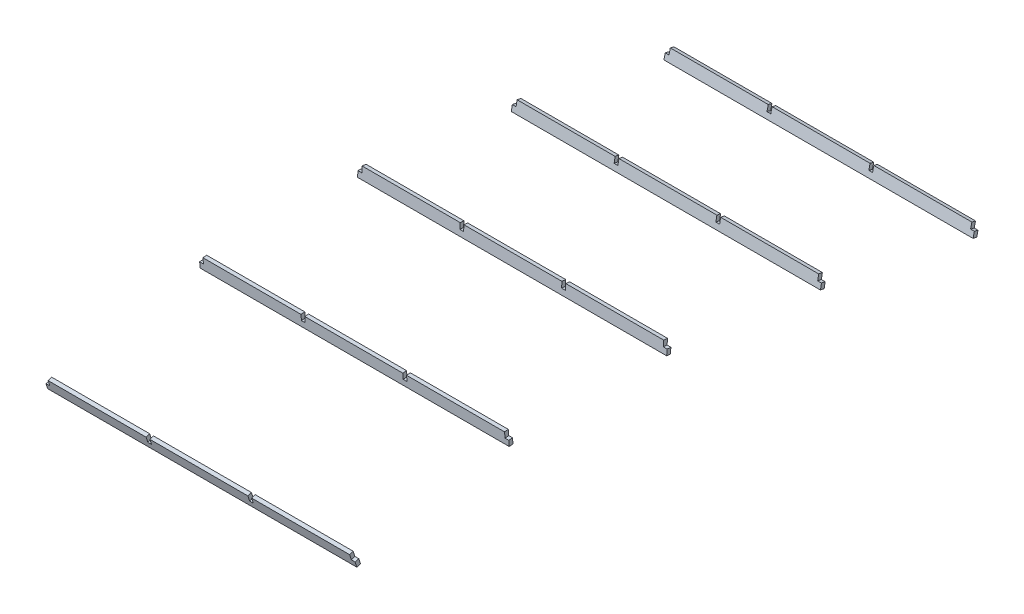
SolidWorks part; units mm, degrees
material "Balsa"
ref_plane "Front" through (0, 0, 0) normal (0, 0, 1) x (1, 0, 0)
ref_plane "Top" through (0, 0, 0) normal (0, 1, 0) x (1, 0, 0)
ref_plane "Right" through (0, 0, 0) normal (1, 0, 0) x (0, 0, -1)
sketch "Sketch1" plane through (0, 0, 0) normal (1, 0, 0) x (0, 0, -1)
  line L0 (603.9897, 31.1863) -> (568.0177, -122.1933) construction
  line L1 (474.8438, 58.0051) -> (472.6476, 45.4964) construction
  line L2 (344.2165, 75.0826) -> (333.6085, -60.2798) construction
  line L3 (221.241, -68.7131) -> (209.8123, 75.4717) construction
  line L4 (78.8208, 51.4601) -> (121.5265, -80.0182) construction
  line L5 (208.3552, 73.7637) -> (211.5203, 74.0146)
  line L6 (77.8013, 49.4598) -> (80.821, 50.4407)
  line L7 (77.8013, 49.4598) -> (80.7439, 40.4007)
  line L8 (80.7439, 40.4007) -> (83.7636, 41.3816)
  line L9 (80.821, 50.4407) -> (83.7636, 41.3816)
  line L10 (77.8013, 49.4598) -> (83.7636, 41.3816) construction
  line L11 (80.7439, 40.4007) -> (80.821, 50.4407) construction
  line L12 (208.3552, 73.7637) -> (209.1079, 64.2685)
  line L13 (209.1079, 64.2685) -> (212.2729, 64.5194)
  line L14 (211.5203, 74.0146) -> (212.2729, 64.5194)
  line L15 (208.3552, 73.7637) -> (212.2729, 64.5194) construction
  line L16 (209.1079, 64.2685) -> (211.5203, 74.0146) construction
  line L17 (342.5098, 73.624) -> (345.6751, 73.3759)
  line L18 (342.5098, 73.624) -> (341.7656, 64.1281)
  line L19 (341.7656, 64.1281) -> (344.9309, 63.88)
  line L20 (345.6751, 73.3759) -> (344.9309, 63.88)
  line L21 (342.5098, 73.624) -> (344.9309, 63.88) construction
  line L22 (341.7656, 64.1281) -> (345.6751, 73.3759) construction
  line L23 (473.0057, 56.716) -> (476.1329, 56.167)
  line L24 (473.0057, 56.716) -> (471.3586, 47.3345)
  line L25 (471.3586, 47.3345) -> (474.4857, 46.7855)
  line L26 (476.1329, 56.167) -> (474.4857, 46.7855)
  line L27 (473.0057, 56.716) -> (474.4857, 46.7855) construction
  line L28 (471.3586, 47.3345) -> (476.1329, 56.167) construction
  line L29 (602.0816, 30.0032) -> (605.1728, 29.2783)
  line L30 (602.0816, 30.0032) -> (599.9068, 20.7299)
  line L31 (599.9068, 20.7299) -> (602.9979, 20.0049)
  line L32 (605.1728, 29.2783) -> (602.9979, 20.0049)
  line L33 (602.0816, 30.0032) -> (602.9979, 20.0049) construction
  line L34 (599.9068, 20.7299) -> (605.1728, 29.2783) construction
  line L35 (79.3112, 49.9502) -> (78.8208, 51.4601) construction
  line L36 (209.9378, 73.8892) -> (209.8123, 75.4717) construction
  line L37 (344.0924, 73.4999) -> (344.2165, 75.0826) construction
  line L38 (474.5693, 56.4415) -> (474.8438, 58.0051) construction
  line L39 (603.6272, 29.6407) -> (603.9897, 31.1863) construction
  spline S0 degree 3 poles (12.1331, -2915.5063) (926.306, 0.9472) (851.2041, -43.6145) (793.7325, -21.0824) (781.4367, -16.2674) (764.957, -10.6639) (744.372, -4.7471) (719.9524, 1.9964) (692.0223, 9.3892) (661.0588, 17.3346) (627.5342, 25.6346) (591.9245, 34.0706) (554.6945, 42.4024) (516.2901, 50.3778) (477.137, 57.7507) (437.6374, 64.289) (398.1712, 69.781) (359.0952, 74.0314) (320.7322, 76.9119) (283.3065, 78.1298) (247.0747, 77.77) (212.2459, 75.9229) (179.1221, 72.6352) (147.9767, 68.1444) (119.1374, 62.5637) (92.9098, 56.0047) (69.5743, 48.6144) (49.3759, 40.5101) (32.5339, 31.8854) (19.2463, 22.934) (10.5195, 14.6895) (6.3234, 8.5527) (5.0144, 5.4603) (4.5923, 4.0442) (1.8078, -10.162) (46.3416, -28.5752) (-2983.583, 247.6782) knots -0.191188 -0.191188 -0.191188 -0.191188 0.003802 0.014472 0.030564 0.051299 0.077028 0.107574 0.142399 0.180921 0.222525 0.266591 0.312515 0.35971 0.407632 0.455773 0.503669 0.550901 0.597096 0.641976 0.685512 0.727353 0.767354 0.805169 0.840471 0.872937 0.902335 0.928425 0.951113 0.970253 0.985871 0.993982 0.996753 0.997907 0.999293 1.048576 1.048576 1.048576 1.048576 only from (806.5263, -25.6355) to (4.3753, 2.3762) construction
  spline S1 degree 3 poles (806.5263, -25.6355) (805.5125, -25.3343) (801.6537, -24.188) (793.7325, -21.0824) (781.4367, -16.2674) (764.957, -10.6639) (744.372, -4.7471) (719.9524, 1.9964) (692.0223, 9.3892) (661.0588, 17.3346) (627.5342, 25.6346) (591.9245, 34.0706) (554.6945, 42.4024) (516.2901, 50.3778) (477.137, 57.7507) (437.6374, 64.289) (398.1712, 69.781) (359.0952, 74.0314) (320.7322, 76.9119) (283.3065, 78.1298) (247.0747, 77.77) (212.2459, 75.9229) (179.1221, 72.6352) (147.9767, 68.1444) (119.1374, 62.5637) (92.9098, 56.0047) (69.5743, 48.6144) (49.3759, 40.5101) (32.5339, 31.8854) (19.2463, 22.934) (10.5195, 14.6895) (6.3234, 8.5527) (5.0144, 5.4603) (4.5923, 4.0442) (4.4178, 3.154) (4.386, 2.5725) (4.3753, 2.3762) knots 0 0 0 0 0.003802 0.014472 0.030564 0.051299 0.077028 0.107574 0.142399 0.180921 0.222525 0.266591 0.312515 0.35971 0.407632 0.455773 0.503669 0.550901 0.597096 0.641976 0.685512 0.727353 0.767354 0.805169 0.840471 0.872937 0.902335 0.928425 0.951113 0.970253 0.985871 0.993982 0.996753 0.997907 0.999293 1 1 1 1
  point P10 (80.7824, 45.4207)
  point P19 (210.3141, 69.1416)
  point P30 (343.7203, 68.752)
  point P37 (473.7457, 51.7507)
  point P45 (602.5398, 25.0041)
  dimension "D1" = 3.175
  dimension "D2" = 3.175
  dimension "D3" = 3.175
  dimension "D4" = 3.175
  dimension "D5" = 3.175
  dimension "D6" = 1.5875
  dimension "D7" = 1.5875
  dimension "D8" = 1.5875
  dimension "D9" = 1.5875
  dimension "D10" = 1.5875
  dimension "D11" = 9.525
  dimension "D12" = 9.525
  dimension "D13" = 9.525
  dimension "D14" = 9.525
  dimension "D15" = 9.525
extrude "Boss-Extrude1" add sketch "Sketch1" along normal up to surface (260.4518 mm away) from offset 1.5875 contours L9 L6 L7 L8 | L20 L17 L18 L19 | L26 L23 L24 L25 | L32 L29 L30 L31 | L5 L14 L13 L12
sketch "Sketch2" plane through (0, 27.5793, -84.9084) normal (0, -0.3089, 0.9511) x (1, 0, 0)
  line L1 (4.7625, 23.0058) -> (1.5875, 23.0058)
  line L2 (4.7625, 23.0058) -> (4.7625, 18.2433)
  line L3 (4.7625, 18.2433) -> (1.5875, 18.2433)
  line L4 (1.5875, 13.4808) -> (262.0393, 13.4808)
  line L5 (262.0393, 13.4808) -> (262.0393, 23.0058)
  line L6 (262.0393, 23.0058) -> (1.5875, 23.0058)
  line L7 (1.5875, 23.0058) -> (1.5875, 13.4808)
  line L8 (1.5875, 13.4808) -> (262.0393, 13.4808) construction
  line L9 (262.0393, 13.4808) -> (262.0393, 23.0058) construction
  line L10 (262.0393, 23.0058) -> (1.5875, 23.0058) construction
  line L11 (1.5875, 23.0058) -> (1.5875, 13.4808) construction
  line L12 (1.5875, 23.0058) -> (1.5875, 18.2433)
  dimension "D2" = 3.175
  dimension "D1" = 0
extrude "Cut-Extrude1" cut sketch "Sketch2" against normal up to next (3.175 mm away)
sketch "Sketch3" plane through (0, 16.8725, -212.8647) normal (0, -0.079, 0.9969) x (1, 0, 0)
  line L0 (1.5875, 57.0697) -> (1.5875, 47.5447) construction
  line L1 (1.5875, 52.3072) -> (4.7625, 52.3072)
  line L2 (1.5875, 52.3072) -> (1.5875, 57.0697)
  line L3 (1.5875, 57.0697) -> (4.7625, 57.0697)
  line L4 (4.7625, 52.3072) -> (4.7625, 57.0697)
  line L5 (262.0393, 57.0697) -> (1.5875, 57.0697) construction
  dimension "D1" = 3.175
sketch "Sketch4" plane through (0, -26.2283, -334.6846) normal (0, 0.0781, 0.9969) x (1, 0, 0)
  line L0 (1.5875, 100.1584) -> (1.5875, 90.6334) construction
  line L1 (1.5875, 95.3959) -> (4.7625, 95.3959)
  line L2 (1.5875, 95.3959) -> (1.5875, 100.1584)
  line L3 (1.5875, 100.1584) -> (4.7625, 100.1584)
  line L4 (4.7625, 95.3959) -> (4.7625, 100.1584)
  line L5 (262.0393, 100.1584) -> (1.5875, 100.1584) construction
  dimension "D1" = 3.175
sketch "Sketch5" plane through (0, -78.8672, -449.2011) normal (0, 0.1729, 0.9849) x (1, 0, 0)
  line L0 (1.5875, 137.657) -> (1.5875, 128.132) construction
  line L1 (1.5875, 132.8945) -> (4.7625, 132.8945)
  line L2 (1.5875, 132.8945) -> (1.5875, 137.657)
  line L3 (1.5875, 137.657) -> (4.7625, 137.657)
  line L4 (4.7625, 132.8945) -> (4.7625, 137.657)
  line L5 (262.0393, 137.657) -> (1.5875, 137.657) construction
  dimension "D1" = 3.175
sketch "Sketch6" plane through (0, -132.2794, -564.0217) normal (0, 0.2283, 0.9736) x (1, 0, 0)
  line L0 (1.5875, 166.6859) -> (1.5875, 157.1609) construction
  line L1 (1.5875, 161.9234) -> (4.7625, 161.9234)
  line L2 (1.5875, 161.9234) -> (1.5875, 166.6859)
  line L3 (1.5875, 166.6859) -> (4.7625, 166.6859)
  line L4 (4.7625, 161.9234) -> (4.7625, 166.6859)
  line L5 (262.0393, 166.6859) -> (1.5875, 166.6859) construction
  dimension "D1" = 3.175
extrude "Cut-Extrude2" cut sketch "Sketch3" against normal up to next (3.175 mm away)
extrude "Cut-Extrude3" cut sketch "Sketch4" against normal up to next (3.175 mm away)
extrude "Cut-Extrude4" cut sketch "Sketch5" against normal up to next (3.175 mm away)
extrude "Cut-Extrude5" cut sketch "Sketch6" against normal up to next (3.175 mm away)
pattern_linear "LPattern1" count 4 spacing 85.7589 along (1, 0, 0) of "Cut-Extrude1", "Cut-Extrude2", "Cut-Extrude3", "Cut-Extrude4", "Cut-Extrude5"
